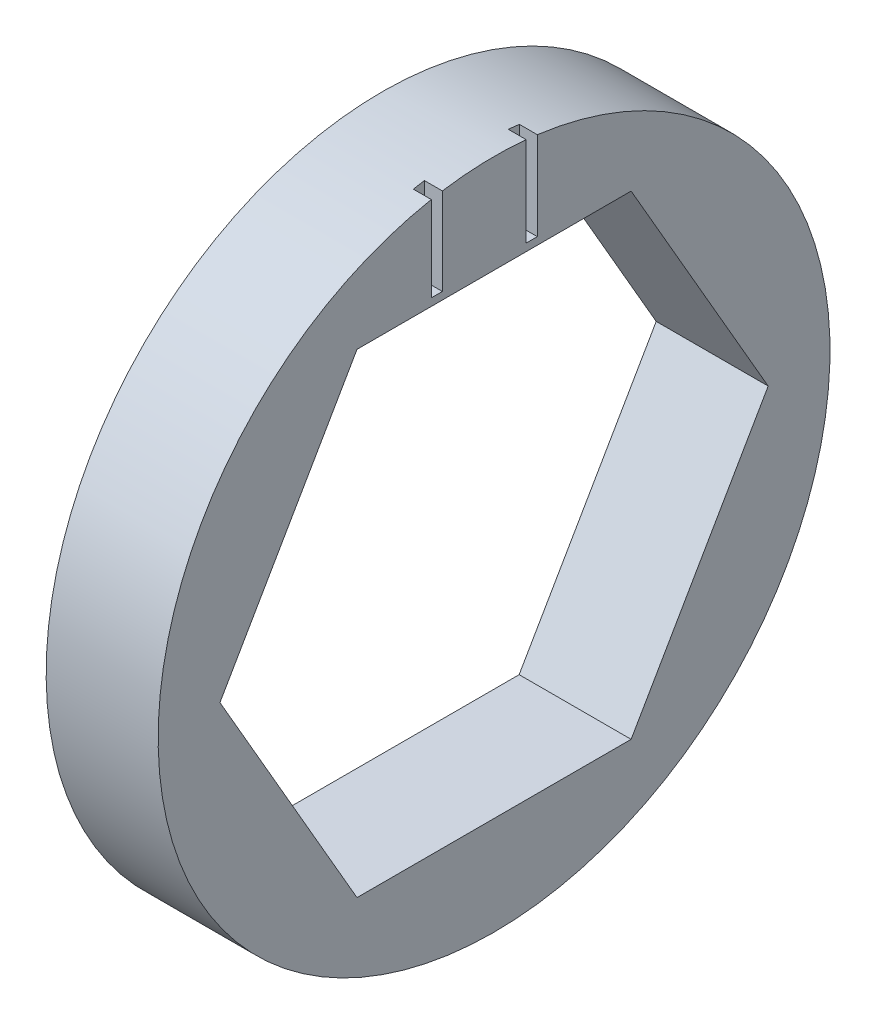
SolidWorks part; units mm, degrees
ref_plane "Front Plane" through (0, 0, 0) normal (0, 0, 1) x (1, 0, 0)
ref_plane "Top Plane" through (0, 0, 0) normal (0, 1, 0) x (1, 0, 0)
ref_plane "Right Plane" through (0, 0, 0) normal (1, 0, 0) x (0, 0, -1)
sketch "Sketch1" plane through (0, 0, 0) normal (1, 0, 0) x (0, 0, -1)
  line L1 (7.7723, 0) -> (3.8861, 6.731)
  line L2 (3.8861, 6.731) -> (-3.8861, 6.731)
  line L3 (-3.8861, 6.731) -> (-7.7723, 0)
  line L4 (-7.7723, 0) -> (-3.8861, -6.731)
  line L5 (-3.8861, -6.731) -> (3.8861, -6.731)
  line L6 (3.8861, -6.731) -> (7.7723, 0)
  circle A0 centre (0, 0) radius 6.731 construction
  circle A1 centre (0, 0) radius 9.525
  dimension "D1" = 13.462
  dimension "D2" = 19.05
extrude "Boss-Extrude1" add sketch "Sketch1" along normal blind 3.175
sketch "Sketch2" plane through (3.175, 0, 0) normal (1, 0, 0) x (0, 0, -1)
  text T0 "11"
extrude "Cut-Extrude1" cut sketch "Sketch2" against normal blind 0.508
